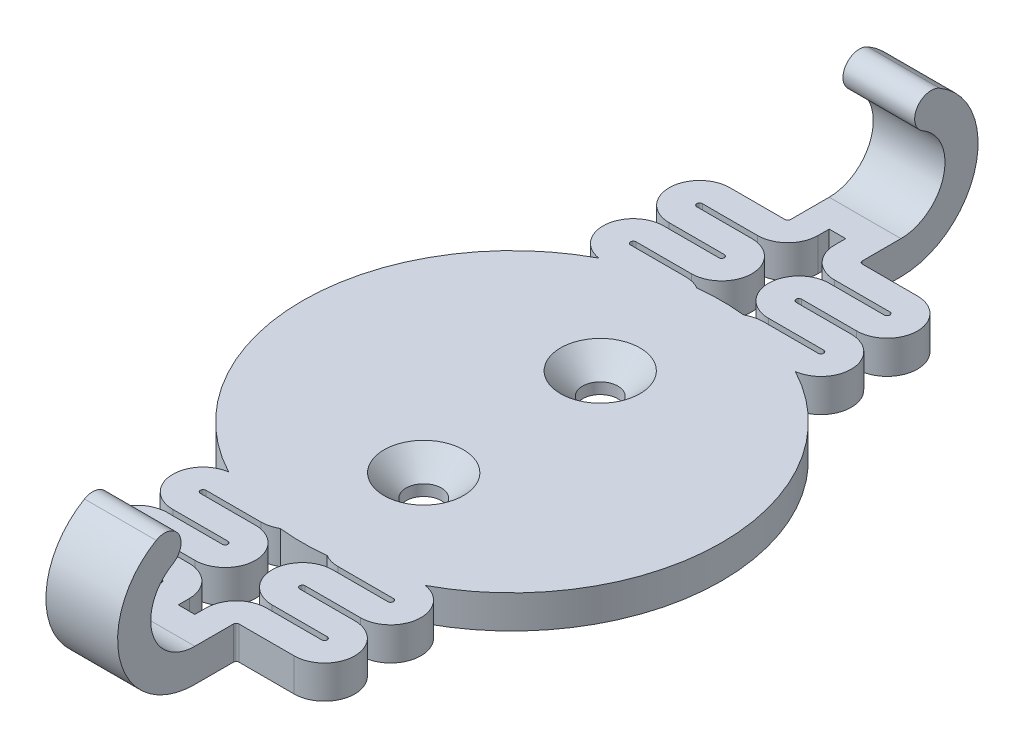
SolidWorks part; units mm, degrees
material "PET"
ref_plane "Front Plane" through (0, 0, 0) normal (0, 0, 1) x (1, 0, 0)
ref_plane "Top Plane" through (0, 0, 0) normal (0, 1, 0) x (1, 0, 0)
ref_plane "Right Plane" through (0, 0, 0) normal (1, 0, 0) x (0, 0, -1)
sketch "Sketch1" plane through (0, 0, 0) normal (0, 1, 0) x (1, 0, 0)
  circle A0 centre (0, 0) radius 19
  dimension "D1" = 38
extrude "Body" add sketch "Sketch1" along normal blind 3
sketch "Sketch2" plane through (0, 0, 0) normal (0, 1, 0) x (1, 0, 0)
  line L0 (0, 0) -> (0, 50000) construction
  line L1 (3.5, 18) -> (8.5, 18)
  line L2 (8.5, 21) -> (3.5, 21)
  line L4 (2, 22.5) -> (0, 22.5) construction
  arc A0 (8.5, 18) -> (8.5, 21) centre (8.5, 19.5) ccw
  arc A1 (3.5, 21) -> (2, 22.5) centre (3.5, 22.5) cw
  arc A3 (3.5, 18) -> (2, 16.5) centre (3.5, 16.5) ccw
  point P10 (10, 19.5)
  dimension "D1" = 2
  dimension "D2" = 3
  dimension "D3" = 18
  dimension "D4" = 8
extrude "Spring profile" add sketch "Sketch2" along normal up to surface (3 mm away) thin up to face at (0, 3, 19) thin type mid plane wall 2.5
pattern_linear "Spring pattern" count 2 spacing 6 along (0, 0, -1) of "Spring profile"
sketch "Sketch5" plane through (0, 0, -28.5) normal (0, 0, -1) x (-1, 0, 0)
  line L1 (-0.75, 0) -> (-3.25, 0)
  line L2 (-0.75, 0) -> (-0.75, 3)
  line L3 (-0.75, 3) -> (-3.25, 3)
  line L4 (-3.25, 0) -> (-3.25, 3)
extrude "Spring extension" add sketch "Sketch5" along normal blind 1
mirror "Mirror1" about plane through (0, 0, 0) normal (0, 0, 1) of "Spring extension", "Spring pattern", "Spring profile"
sketch "Sketch4" plane through (0, 0, 0) normal (1, 0, 0) x (0, 0, -1)
  line L3 (32, 7) -> (32, 3) construction
  line L4 (32, 0) -> (29.5, 0)
  line L5 (36, 29.0892) -> (36, -0.4085) construction
  line L6 (29.5, 0) -> (29.5, 3)
  line L7 (32, 0) -> (0, 0) construction
  line L9 (29.5, 3) -> (32, 3)
  line L10 (34.75, 11.7631) -> (32, 7) construction
  arc A0 (32, 3) -> (34, 10.4641) centre (32, 7) ccw
  arc A1 (32, 0) -> (35.5, 13.0622) centre (32, 7) ccw
  arc A2 (34, 10.4641) -> (35.5, 13.0622) centre (34.75, 11.7631) cw
  dimension "D1" = 150
  dimension "D2" = 36
  dimension "D3" = 4
extrude "Clamp" add sketch "Sketch4" along normal mid plane 6.5
mirror "Mirror2" about plane through (0, 0, 0) normal (0, 0, 1) of "Clamp"
sketch "Sketch6" plane through (0, 0, 0) normal (0, 1, 0) x (1, 0, 0)
  line L0 (0, -8) -> (0, 8) construction
  circle A0 centre (0, -8) radius 1.6
  circle A1 centre (0, 8) radius 1.6
  point P4 (0, 0)
  dimension "D2" = 3.2
  dimension "D1" = 16
extrude "Screw holes" cut sketch "Sketch6" along normal through all
chamfer "Screw chamfer" distance 2 angle 45 2 edges at (0, 3, 9.6) (0, 3, -6.4)
